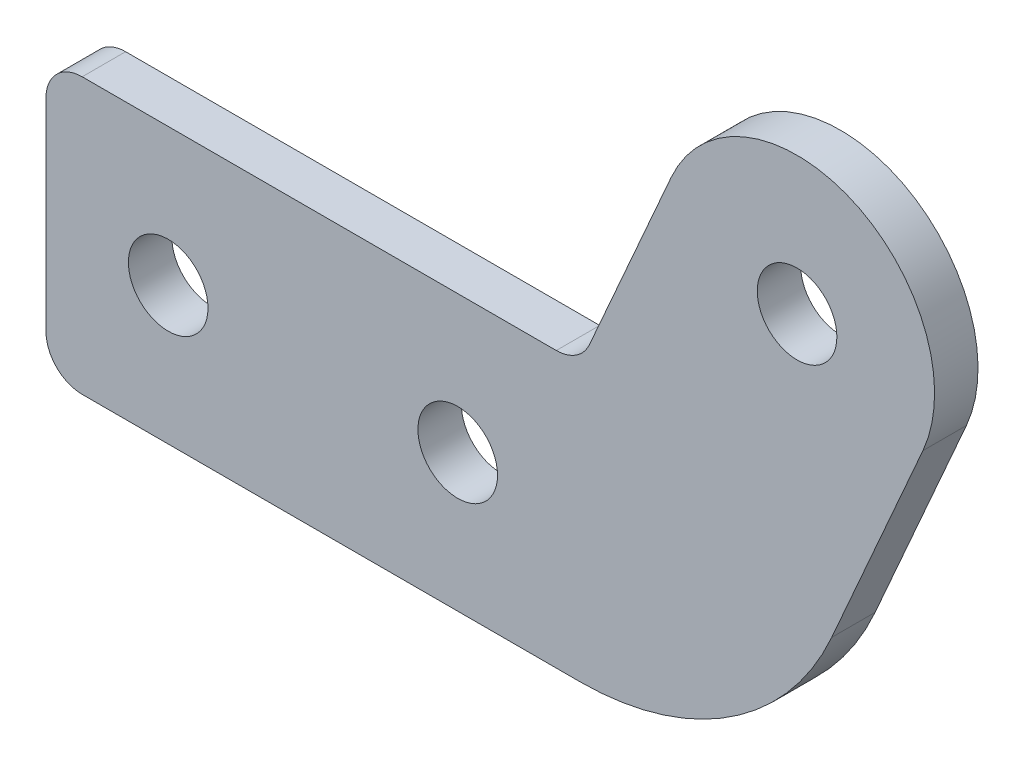
SolidWorks part; units mm, degrees
ref_plane "Front Plane" through (0, 0, 0) normal (0, 0, 1) x (1, 0, 0)
ref_plane "Top Plane" through (0, 0, 0) normal (0, 1, 0) x (1, 0, 0)
ref_plane "Right Plane" through (0, 0, 0) normal (1, 0, 0) x (0, 0, -1)
sketch "Sketch1" plane through (0, 0, 0) normal (0, 0, 1) x (1, 0, 0)
  line L0 (-51.88, -20) -> (-5.9425, -20) construction
  line L1 (8.6953, -3.8266) -> (2.3905, -18.1531)
  line L2 (-51.88, -10.5) -> (-51.88, -29.5)
  line L3 (-51.88, -10.5) -> (-15, -10.5)
  line L4 (-51.88, -23.5) -> (-51.88, -16.5) construction
  line L5 (-15, -29.5) -> (-515, -29.5) construction
  line L6 (-15, -29.5) -> (-51.88, -29.5)
  line L7 (-15, 9.5) -> (-515, 9.5) construction
  line L8 (-15, -15.42) -> (-15, -4.58) construction
  line L9 (-15, -10.5) -> (-8.6953, 3.8266)
  arc A0 (8.6953, -3.8266) -> (-8.6953, 3.8266) centre (0, 0) ccw
  arc A1 (2.3905, -18.1531) -> (-15, -29.5) centre (-15, -10.5) cw
extrude "Boss-Extrude1" add sketch "Sketch1" along normal blind 3
hole_wizard "M5 Clearance Hole1" positions "Sketch5" profile "Sketch4" hole size "M5" standard "ISO" end condition up to next
sketch "Sketch5" plane through (0, 0, 3) normal (0, 0, 1) x (1, 0, 0)
  circle A0 centre (-43.44, -20) radius 2.1 construction
  point P0 (-43.44, -20)
sketch "Sketch4" plane through (-43.44, -20, 3) normal (1, 0, 0) x (0, -1, 0)
  line L0 (0, 0) -> (0, 3)
  line L1 (0, 3) -> (2.75, 3)
  line L2 (2.75, 3) -> (2.75, 0)
  line L5 (2.75, 0) -> (0, 0)
  line L11 (0, -6.35) -> (0, 107.95) construction
  dimension "Thru Hole Dia." = 5.5
  dimension "Thru Hole Depth" = 3
hole_wizard "M5 Clearance Hole2" positions "Sketch7" profile "Sketch6" hole size "M5" standard "ISO" end condition up to next
sketch "Sketch7" plane through (0, 0, 3) normal (0, 0, 1) x (1, 0, 0)
  circle A0 centre (-23.44, -20) radius 2.1 construction
  point P0 (-23.44, -20)
sketch "Sketch6" plane through (-23.44, -20, 3) normal (1, 0, 0) x (0, -1, 0)
  line L0 (0, 0) -> (0, 3)
  line L1 (0, 3) -> (2.75, 3)
  line L2 (2.75, 3) -> (2.75, 0)
  line L5 (2.75, 0) -> (0, 0)
  line L11 (0, -6.35) -> (0, 107.95) construction
  dimension "Thru Hole Dia." = 5.5
  dimension "Thru Hole Depth" = 3
hole_wizard "M5 Clearance Hole3" positions "Sketch9" profile "Sketch8" hole size "M5" standard "ISO" end condition up to next
sketch "Sketch9" plane through (0, 0, 3) normal (0, 0, 1) x (1, 0, 0)
  point P0 (0, 0)
sketch "Sketch8" plane through (0, 0, 3) normal (1, 0, 0) x (0, -1, 0)
  line L0 (0, 0) -> (0, 3)
  line L1 (0, 3) -> (2.75, 3)
  line L2 (2.75, 3) -> (2.75, 0)
  line L5 (2.75, 0) -> (0, 0)
  line L11 (0, -6.35) -> (0, 107.95) construction
  dimension "Thru Hole Dia." = 5.5
  dimension "Thru Hole Depth" = 3
fillet "Fillet2" radius 2.5 3 edges at (-51.88, -29.5, 1.5) (-51.88, -10.5, 1.5) (-15, -10.5, 1.5)
